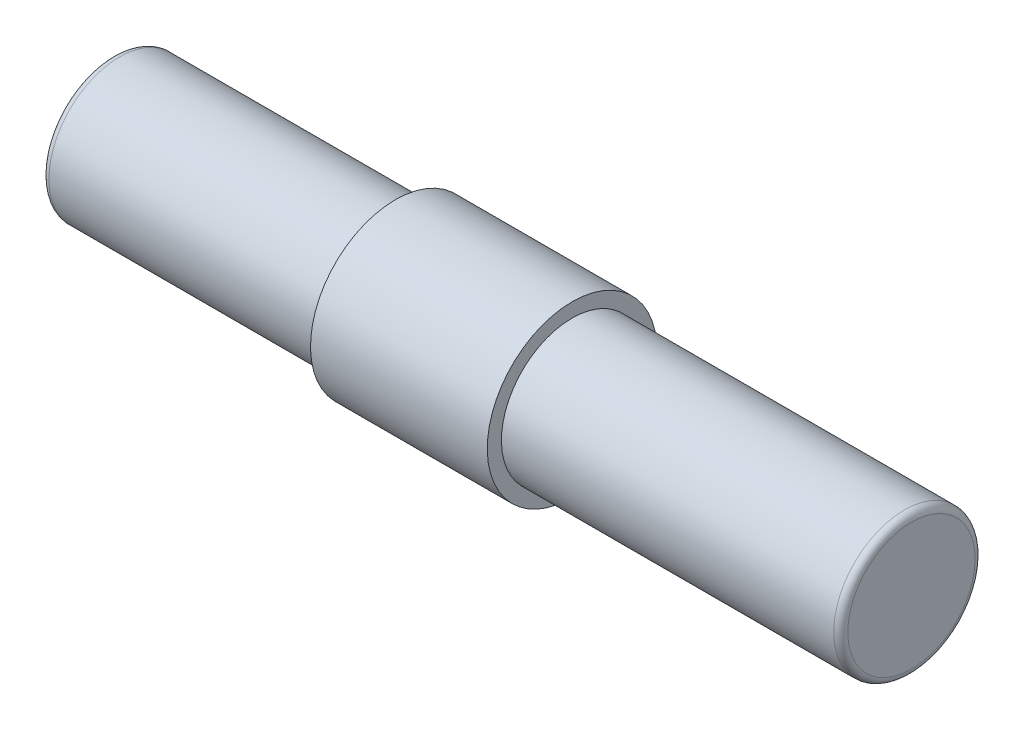
SolidWorks part; units mm, degrees
material "1.5714 (16NiCr4)"
ref_plane "Ebene vorne" through (0, 0, 0) normal (0, 0, 1) x (1, 0, 0)
ref_plane "Ebene oben" through (0, 0, 0) normal (0, 1, 0) x (1, 0, 0)
ref_plane "Ebene rechts" through (0, 0, 0) normal (1, 0, 0) x (0, 0, -1)
sketch "Skizze1" plane through (0, 0, 0) normal (0, 0, 1) x (1, 0, 0)
  line L0 (-57.4684, 0) -> (-57.4684, 5)
  line L1 (-57.4684, 5) -> (-37.4684, 5)
  line L2 (-37.4684, 5) -> (-37.4684, 6)
  line L3 (-37.4684, 6) -> (-24.9684, 6)
  line L4 (-24.9684, 6) -> (-24.9684, 5)
  line L5 (-24.9684, 5) -> (-0.9684, 5)
  line L6 (-0.9684, 5) -> (-0.9684, 0)
  line L7 (-0.9684, 0) -> (-57.4684, 0)
  dimension "D1" = 5
  dimension "D2" = 20
  dimension "D3" = 12.5
  dimension "D4" = 24
  dimension "D5" = 6
  dimension "D6" = 5
revolve "Rotation1" add sketch "Skizze1" angle 360 about L7
fillet "Verrundung1" radius 0.5 2 edges at (-0.9684, 5, 0) (-57.4684, 5, 0)
